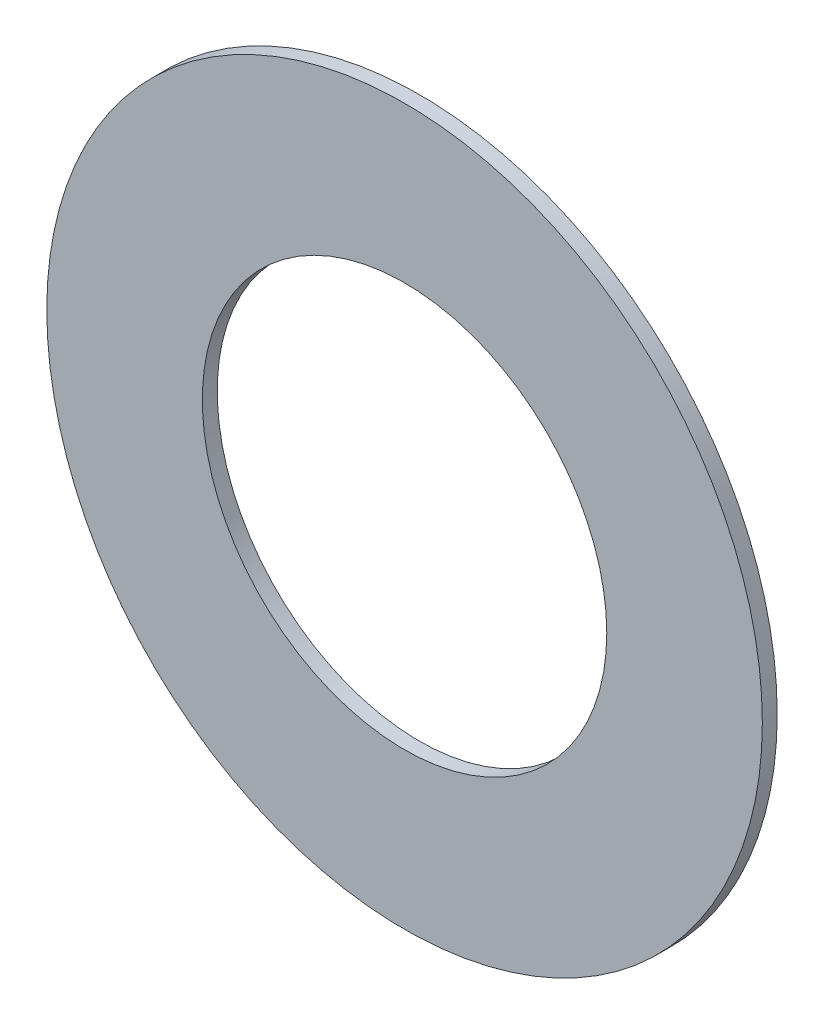
SolidWorks part; units mm, degrees
material "Chrome Stainless Steel"
ref_plane "Front Plane" through (0, 0, 0) normal (0, 0, 1) x (1, 0, 0)
ref_plane "Top Plane" through (0, 0, 0) normal (0, 1, 0) x (1, 0, 0)
ref_plane "Right Plane" through (0, 0, 0) normal (1, 0, 0) x (0, 0, -1)
sketch "Sketch1" plane through (0, 0, 0) normal (0, 0, 1) x (1, 0, 0)
  circle A0 centre (0, 0) radius 20.6375
  circle A1 centre (0, 0) radius 36.5125
  dimension "D1" = 41.275
  dimension "D2" = 73.025
extrude "Boss-Extrude1" add sketch "Sketch1" along normal blind 1.5189
